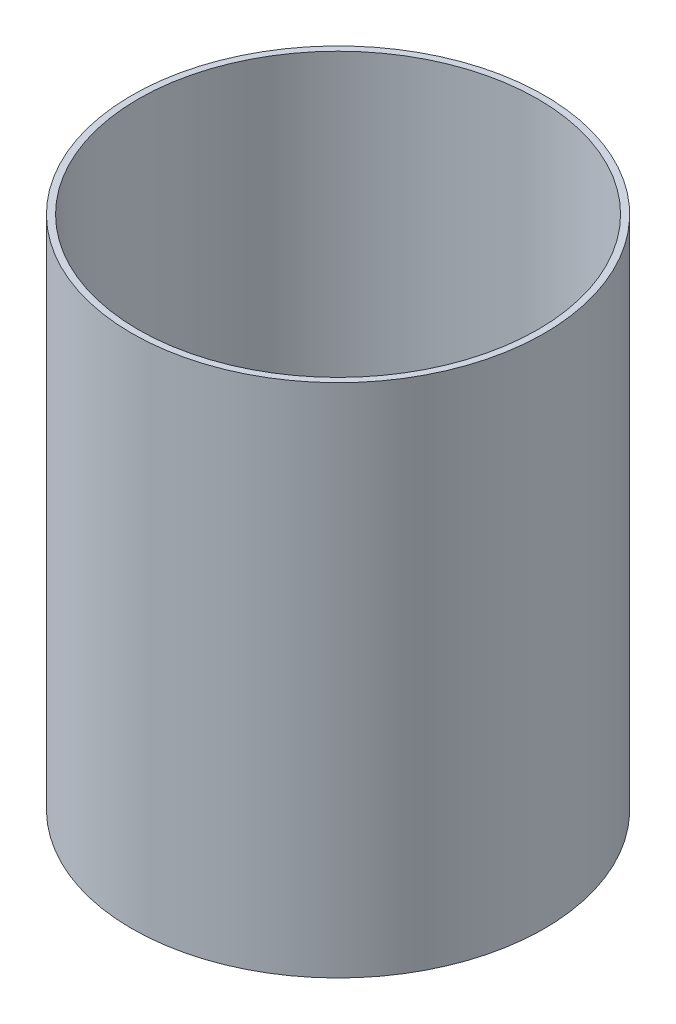
SolidWorks part; units mm, degrees
material "6061-T6 (SS)"
ref_plane "Front Plane" through (0, 0, 0) normal (0, 0, 1) x (1, 0, 0)
ref_plane "Top Plane" through (0, 0, 0) normal (0, 1, 0) x (1, 0, 0)
ref_plane "Right Plane" through (0, 0, 0) normal (1, 0, 0) x (0, 0, -1)
sketch "Sketch1" plane through (0, 0, 0) normal (0, 1, 0) x (1, 0, 0)
  line L0 (-65.3387, 0) -> (65.3387, 0) construction
  line L1 (0, -71.0349) -> (0, 71.0349) construction
  circle A0 centre (0, 0) radius 98.425
  circle A1 centre (0, 0) radius 101.6
  point P4 (0, 0)
  point P8 (0, 0)
  dimension "D1" = 196.85
  dimension "D2" = 203.2
extrude "Boss-Extrude1" add sketch "Sketch1" along normal mid plane 254
sketch "Sketch2" plane through (0, 127, 0) normal (0, 1, 0) x (1, 0, 0)
  line L0 (-150.6772, 0) -> (150.6772, 0) construction
  line L1 (0, -106.7355) -> (0, 106.7355) construction
  line L2 (0, 0) -> (-112.331, 169.3281)
  line L3 (0, 0) -> (-112.331, -169.3281)
  line L4 (-112.331, 169.3281) -> (-112.331, -169.3281)
  point P4 (0, 0)
  point P8 (0, 0)
  dimension "D1" = 33.56
  dimension "D2" = 203.2
extrude "Cut-Extrude1" [suppressed] cut sketch "Sketch2" against normal blind 25.4
chamfer "Chamfer1" [suppressed] distance 10 angle 56
